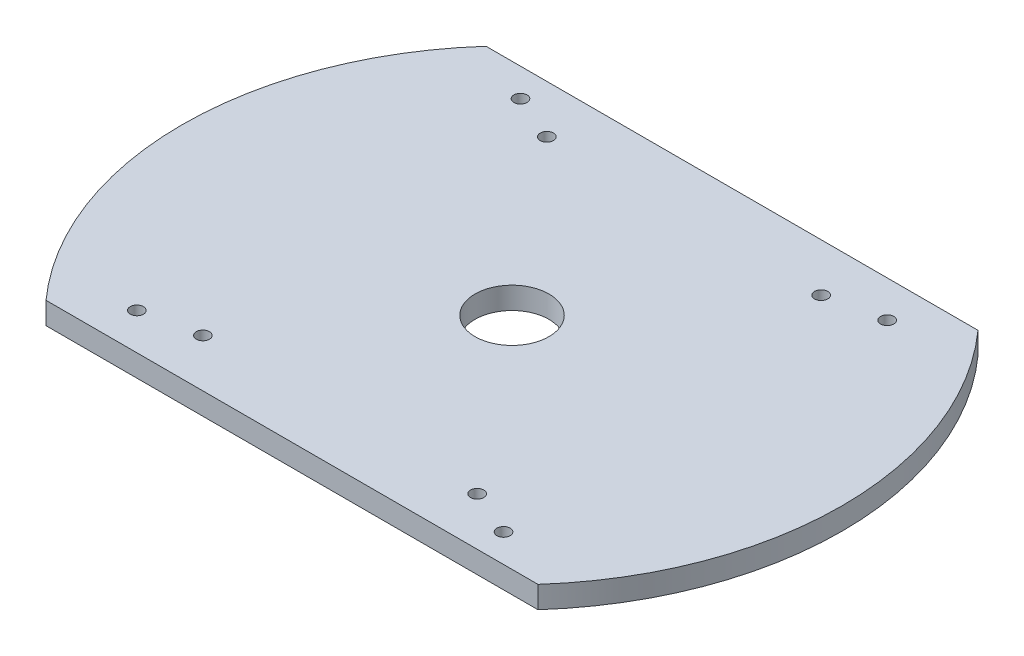
SolidWorks part; units mm, degrees
ref_plane "Front Plane" through (0, 0, 0) normal (0, 0, 1) x (1, 0, 0)
ref_plane "Top Plane" through (0, 0, 0) normal (0, 1, 0) x (1, 0, 0)
ref_plane "Right Plane" through (0, 0, 0) normal (1, 0, 0) x (0, 0, -1)
sketch "Sketch1" plane through (0, 0, 0) normal (0, 1, 0) x (1, 0, 0)
  line L0 (-41.6647, 43.5906) -> (0, 0) construction
  line L1 (-41.6647, 43.5906) -> (-41.6647, 39.0906) construction
  line L2 (-41.6647, 39.0906) -> (-31.1647, 39.0906) construction
  line L3 (0, 39.0906) -> (0, 0) construction
  line L4 (0, 0) -> (37.6023, 0) construction
  circle A0 centre (0, 0) radius 75
  circle A1 centre (-41.6647, 43.5906) radius 1.5
  circle A2 centre (43.5906, 41.6647) radius 1.5
  circle A3 centre (41.6647, -43.5906) radius 1.5
  circle A4 centre (-43.5906, -41.6647) radius 1.5
  circle A5 centre (-31.1647, 39.0906) radius 1.5
  circle A7 centre (43.5906, 41.6647) radius 1.5
  circle A9 centre (41.6647, -43.5906) radius 1.5
  circle A11 centre (-43.5906, -41.6647) radius 1.5
  circle A12 centre (0, 0) radius 8.4
  circle A13 centre (31.1647, 39.0906) radius 1.5
  circle A14 centre (39.0906, 31.1647) radius 1.5 [skipped]
  circle A15 centre (31.1647, -39.0906) radius 1.5 [skipped]
  circle A16 centre (-39.0906, -31.1647) radius 1.5 [skipped]
  circle A17 centre (31.1647, -39.0906) radius 1.5
  circle A18 centre (-31.1647, -39.0906) radius 1.5
  point P14 (0, 0)
  point P30 (0, 0)
  dimension "D1" = 150
  dimension "D2" = 3
  dimension "D8" = 16.8
  dimension "D3" = 60.3
  dimension "D5" = 4.5
  dimension "D6" = 10.5
  dimension "D4" = 4
  dimension "D7" = 4
extrude "Boss-Extrude1" add sketch "Sketch1" along normal blind 5
sketch "Sketch3" plane through (0, 5, 0) normal (0, 1, 0) x (1, 0, 0)
  line L0 (0, 0) -> (0, 50)
  line L1 (0, 50) -> (-65.9769, 50)
  line L2 (0, 50) -> (71.3543, 50)
  line L3 (0, 0) -> (0, -50)
  line L4 (0, -50) -> (67.8383, -50)
  line L5 (0, -50) -> (-71.1475, -50)
  arc A0 (-65.9769, 50) -> (71.3543, 50) centre (2.6887, -24.5662) cw
  arc A1 (-71.1475, -50) -> (67.8383, -50) centre (-1.6546, 13.6778) ccw
  circle M10 centre (0, 0) radius 75
  dimension "D1" = 50
  dimension "D2" = 50
extrude "Cut-Extrude1" cut sketch "Sketch3" against normal blind 10 contours L1 L2 M10 | L4 L5 M10
